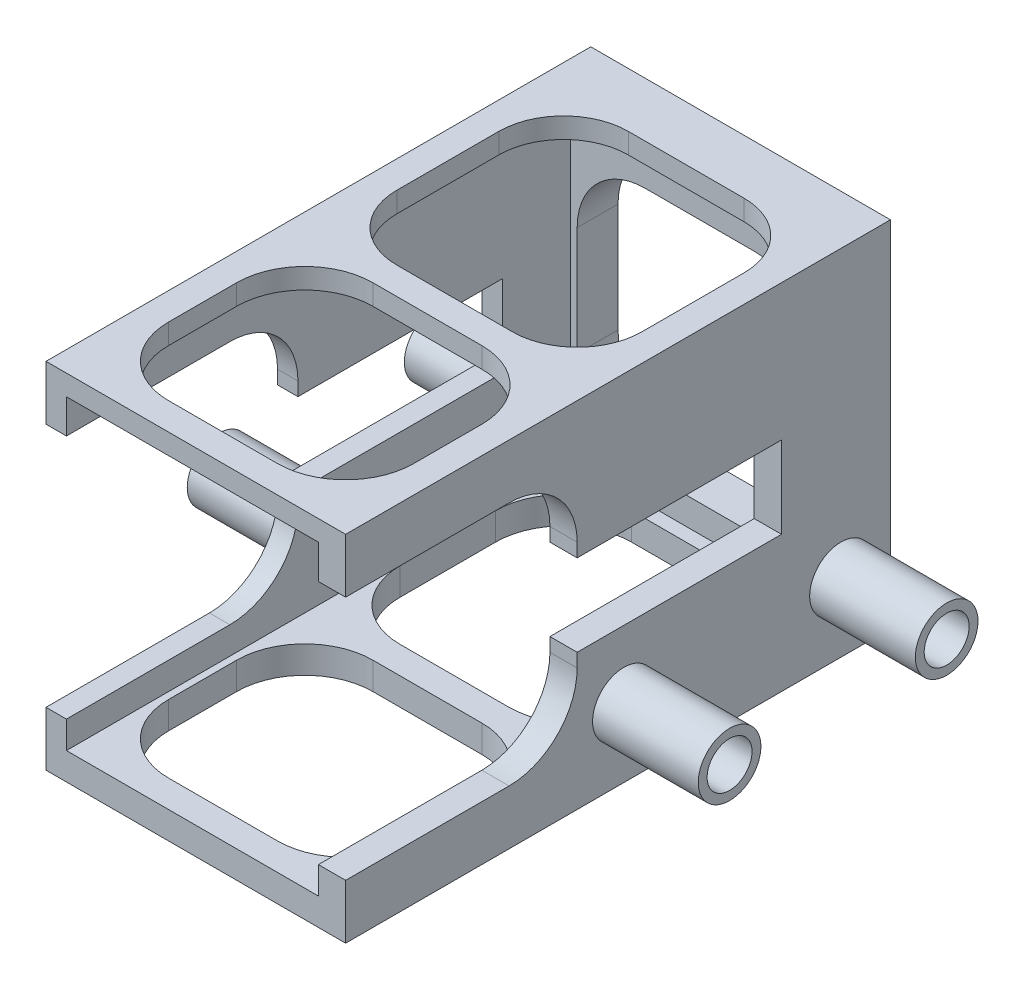
SolidWorks part; units mm, degrees
ref_plane "Front Plane" through (0, 0, 0) normal (0, 0, 1) x (1, 0, 0)
ref_plane "Top Plane" through (0, 0, 0) normal (0, 1, 0) x (1, 0, 0)
ref_plane "Right Plane" through (0, 0, 0) normal (1, 0, 0) x (0, 0, -1)
sketch "Sketch1" plane through (0, 0, 0) normal (0, 0, 1) x (1, 0, 0)
  line L0 (0, 0) -> (22, 0)
  line L1 (22, 0) -> (22, 26)
  line L2 (22, 26) -> (0, 26)
  line L3 (0, 26) -> (0, 0)
  dimension "D1" = 26
  dimension "D2" = 22
extrude "Boss-Extrude1" add sketch "Sketch1" along normal blind 40 contours L2 L3 L0 L1
sketch "Sketch2" plane through (0, 0, 40) normal (0, 0, 1) x (1, 0, 0)
  line L0 (1.5, 24.5) -> (1.5, 2)
  line L1 (1.5, 2) -> (20, 2)
  line L2 (20, 2) -> (20, 24.5)
  line L3 (20, 24.5) -> (1.5, 24.5)
  line L4 (0, 26) -> (0, 0) construction
  line L8 (22, 26) -> (0, 26) construction
  dimension "D1" = 18.5
  dimension "D2" = 1.5
  dimension "D3" = 22.5
  dimension "D4" = 1.5
extrude "Cut-Extrude1" cut sketch "Sketch2" against normal blind 37
sketch "Sketch6" plane through (0, 0, 0) normal (0, 0, -1) x (-1, 0, 0)
  line L0 (-15, 22) -> (-7, 22)
  line L3 (-20, 9) -> (-20, 17)
  line L4 (-2, 17) -> (-2, 9)
  line L5 (-7, 4) -> (-15, 4)
  line L6 (-22, 0) -> (-22, 26) construction
  line L8 (-22, 26) -> (0, 26) construction
  arc A0 (-15, 22) -> (-20, 17) centre (-15, 17) ccw
  arc A1 (-7, 22) -> (-2, 17) centre (-7, 17) cw
  arc A2 (-2, 9) -> (-7, 4) centre (-7, 9) cw
  arc A3 (-15, 4) -> (-20, 9) centre (-15, 9) cw
  point P10 (-20, 22)
  point P13 (-2, 22)
  point P18 (-20, 4)
  dimension "D5" = 5
  dimension "D6" = 5
  dimension "D7" = 5
  dimension "D8" = 5
  dimension "D1" = 18
  dimension "D2" = 18
  dimension "D3" = 2
  dimension "D4" = 4
extrude "Cut-Extrude2" cut sketch "Sketch6" against normal up to next
sketch "Sketch7" plane through (22, 0, 0) normal (1, 0, 0) x (0, 0, -1)
  line L0 (-23, 16) -> (-8, 16)
  line L1 (-40, 0) -> (-40, 26) construction
  line L2 (-8, 16) -> (-8, 10)
  line L3 (-8, 10) -> (-23, 10)
  line L4 (-40, 10) -> (-40, 16)
  line L5 (-40, 26) -> (0, 26) construction
  line L6 (-28, 22) -> (-40, 22)
  line L7 (-40, 22) -> (-40, 4)
  line L8 (-40, 4) -> (-28, 4)
  line L9 (-23, 9) -> (-23, 10)
  line L10 (-40, 0) -> (0, 0) construction
  line L11 (-23, 16) -> (-23, 17)
  arc A0 (-28, 4) -> (-23, 9) centre (-28, 9) ccw
  arc A1 (-28, 22) -> (-23, 17) centre (-28, 17) cw
  point P16 (-23, 4)
  point P19 (-23, 22)
  line M7 (-40, 26) -> (-40, 0)
  dimension "D7" = 5
  dimension "D8" = 5
  dimension "D1" = 32
  dimension "D2" = 6
  dimension "D3" = 10
  dimension "D4" = 17
  dimension "D5" = 18
  dimension "D6" = 4
extrude "Cut-Extrude3" cut sketch "Sketch7" along direction (-1, 0, 0) on the side against the normal up to next (2 mm away) contours A1 L6 L8 A0 L9 L3 L2 L0 L11 M7
sketch "Sketch8" plane through (0, 0, 0) normal (-1, 0, 0) x (0, 0, 1)
  line L0 (23, 16) -> (8, 16)
  line L1 (40, 26) -> (40, 0) construction
  line L2 (8, 16) -> (8, 10)
  line L3 (8, 10) -> (23, 10)
  line L5 (40, 26) -> (0, 26) construction
  line L6 (40, 22) -> (40, 4)
  line L7 (40, 4) -> (28, 4)
  line L8 (23, 9) -> (23, 10)
  line L9 (28, 22) -> (40, 22)
  line L10 (40, 0) -> (0, 0) construction
  line L11 (23, 16) -> (23, 17)
  line L12 (40, 22) -> (40, 4)
  arc A0 (23, 17) -> (28, 22) centre (28, 17) cw
  arc A1 (28, 4) -> (23, 9) centre (28, 9) cw
  point P16 (23, 22)
  point P19 (23, 4)
  line M6 (40, 0) -> (40, 26)
  dimension "D7" = 5
  dimension "D8" = 5
  dimension "D2" = 6
  dimension "D3" = 10
  dimension "D4" = 17
  dimension "D5" = 18
  dimension "D6" = 4
extrude "Cut-Extrude4" cut sketch "Sketch8" along direction (1, 0, 0) on the side against the normal up to next (1.5 mm away) contours A1 L7 L9 A0 L11 L0 L2 L3 L8 M6
sketch "Sketch9" plane through (0, 26, 0) normal (0, 1, 0) x (1, 0, 0)
  line L2 (7, -23) -> (15, -23)
  line L7 (2, -16.2466) -> (2, -8.7534)
  line L8 (6.7534, -4) -> (15.2466, -4)
  line L9 (20, -8.7534) -> (20, -16.2466)
  line L10 (15.2466, -21) -> (6.7534, -21)
  line L11 (2, -28) -> (2, -33)
  line L12 (7, -38) -> (15, -38)
  line L13 (20, -33) -> (20, -28)
  line L14 (22, -40) -> (0, -40) construction
  arc A0 (2, -28) -> (7, -23) centre (7, -28) cw
  arc A1 (15, -23) -> (20, -28) centre (15, -28) cw
  arc A2 (2, -8.7534) -> (6.7534, -4) centre (6.7534, -8.7534) cw
  arc A3 (15.2466, -4) -> (20, -8.7534) centre (15.2466, -8.7534) cw
  arc A4 (20, -16.2466) -> (15.2466, -21) centre (15.2466, -16.2466) cw
  arc A5 (2, -16.2466) -> (6.7534, -21) centre (6.7534, -16.2466) ccw
  arc A6 (2, -33) -> (7, -38) centre (7, -33) ccw
  arc A7 (15, -38) -> (20, -33) centre (15, -33) ccw
  point P12 (2, -23)
  point P13 (20, -23)
  point P20 (2, -4)
  point P27 (2, -21)
  dimension "D4" = 5
  dimension "D5" = 5
  dimension "D8" = 4.7534
  dimension "D9" = 4.7534
  dimension "D10" = 4.7534
  dimension "D11" = 4.7534
  dimension "D12" = 5
  dimension "D13" = 5
  dimension "D2" = 18
  dimension "D3" = 2
  dimension "D6" = 17
  dimension "D7" = 2
extrude "Cut-Extrude5" cut sketch "Sketch9" against normal up to next
sketch "Sketch11" plane through (0, 0, 0) normal (0, -1, 0) x (1, 0, 0)
  line L2 (7, 23) -> (15, 23)
  line L6 (2, 16) -> (2, 9)
  line L7 (7, 4) -> (15, 4)
  line L8 (20, 9) -> (20, 16)
  line L9 (15, 21) -> (7, 21)
  line L10 (2, 28) -> (2, 33)
  line L11 (7, 38) -> (15, 38)
  line L12 (20, 33) -> (20, 28)
  line L13 (0, 40) -> (22, 40) construction
  arc A0 (15, 23) -> (20, 28) centre (15, 28) ccw
  arc A1 (2, 28) -> (7, 23) centre (7, 28) ccw
  arc A2 (2, 16) -> (7, 21) centre (7, 16) cw
  arc A3 (20, 16) -> (15, 21) centre (15, 16) ccw
  arc A4 (2, 9) -> (7, 4) centre (7, 9) ccw
  arc A5 (15, 4) -> (20, 9) centre (15, 9) ccw
  arc A6 (2, 33) -> (7, 38) centre (7, 33) cw
  arc A7 (15, 38) -> (20, 33) centre (15, 33) cw
  point P14 (20, 23)
  point P17 (2, 23)
  point P20 (2, 21)
  point P25 (2, 4)
  dimension "D6" = 5
  dimension "D7" = 5
  dimension "D8" = 5
  dimension "D9" = 5
  dimension "D10" = 5
  dimension "D11" = 5
  dimension "D3" = 5
  dimension "D12" = 5
  dimension "D1" = 18
  dimension "D2" = 2
  dimension "D4" = 17
  dimension "D5" = 2
extrude "Cut-Extrude6" cut sketch "Sketch11" against normal up to next
sketch "Sketch12" plane through (0, 0, 0) normal (-1, 0, 0) x (0, 0, 1)
  circle A0 centre (3.63, 5.03) radius 2.3
  circle A2 centre (19.57, 5.03) radius 2.3
  dimension "D1" = 4.6
  dimension "D3" = 4.6
extrude "Boss-Extrude2" add sketch "Sketch12" along normal blind 7.76
sketch "Sketch14" plane through (-7.76, 0, 0) normal (-1, 0, 0) x (0, 0, 1)
  circle A0 centre (3.63, 5.03) radius 1.65
  dimension "D1" = 3.3
extrude "Cut-Extrude9" cut sketch "Sketch14" against normal blind 7.76
sketch "Sketch16" plane through (-7.76, 0, 0) normal (-1, 0, 0) x (0, 0, 1)
  circle A0 centre (19.57, 5.03) radius 1.65
  dimension "D1" = 3.3
extrude "Cut-Extrude11" cut sketch "Sketch16" against normal blind 7.76
sketch "Sketch17" plane through (22, 0, 0) normal (1, 0, 0) x (0, 0, -1)
  line L0 (-8, 10) -> (-23, 10) construction
  circle A0 centre (-3.63, 5.03) radius 2.3
  circle A2 centre (-19.57, 5.03) radius 2.3
  dimension "D1" = 4.6
  dimension "D3" = 4.6
  dimension "D4" = 4.97
  dimension "D6" = 4.97
extrude "Boss-Extrude3" add sketch "Sketch17" along normal blind 7.76
sketch "Sketch20" plane through (29.76, 0, 0) normal (1, 0, 0) x (0, 0, -1)
  circle A0 centre (-3.63, 5.03) radius 1.65
  circle A2 centre (-19.57, 5.03) radius 1.65
  dimension "D1" = 3.3
  dimension "D3" = 3.3
extrude "Cut-Extrude12" cut sketch "Sketch20" against normal blind 7.76
sketch "Sketch21" plane through (-7.76, 0, 0) normal (-1, 0, 0) x (0, 0, 1)
sketch "Sketch23" plane through (29.76, 0, 0) normal (1, 0, 0) x (0, 0, -1)
  circle A0 centre (-19.57, 5.03) radius 2.4
  circle A1 centre (-3.63, 5.03) radius 2.4
  dimension "D1" = 4.8
  dimension "D2" = 4.8
